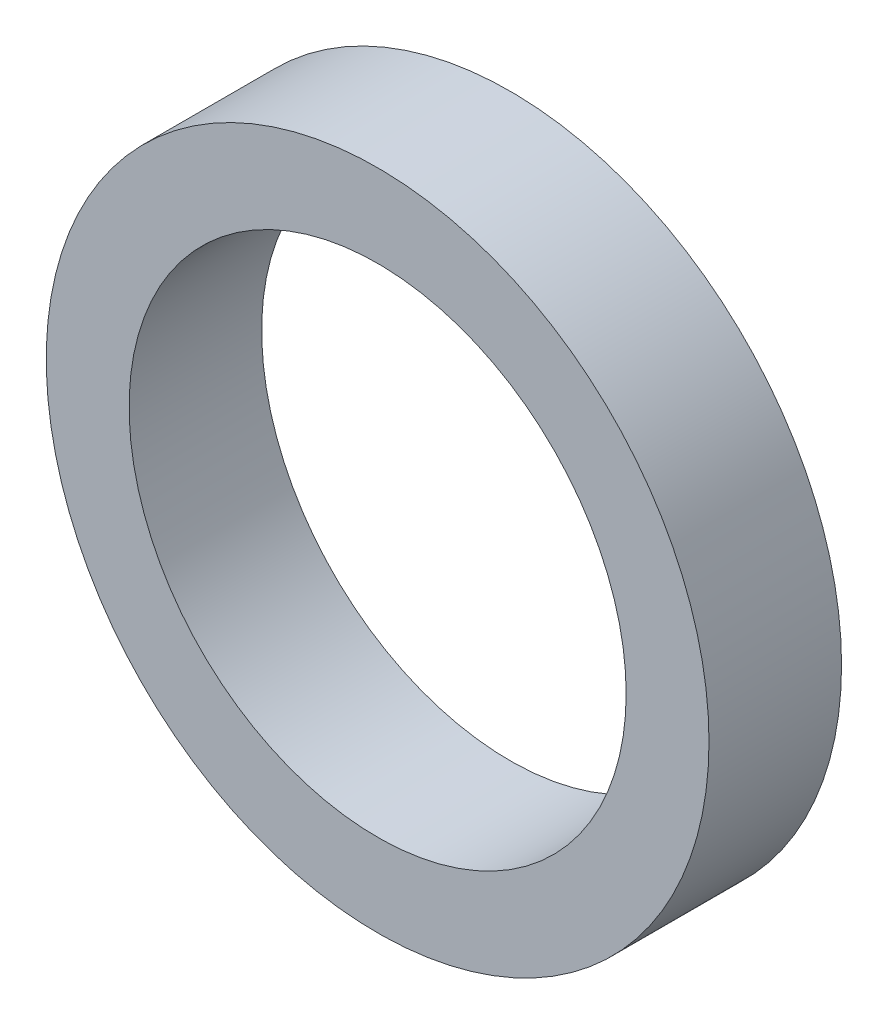
SolidWorks part; units mm, degrees
ref_plane "Front" through (0, 0, 0) normal (0, 0, 1) x (1, 0, 0)
ref_plane "Top" through (0, 0, 0) normal (0, 1, 0) x (1, 0, 0)
ref_plane "Right" through (0, 0, 0) normal (1, 0, 0) x (0, 0, -1)
sketch "Sketch2" plane through (0, 0, 0) normal (0, 0, 1) x (1, 0, 0)
  circle A0 centre (0, 0) radius 9.525
  circle A1 centre (0, 0) radius 12.7
  dimension "D1" = 19.05
  dimension "D2" = 25.4
extrude "Boss-Extrude1" add sketch "Sketch2" along normal blind 5.08
